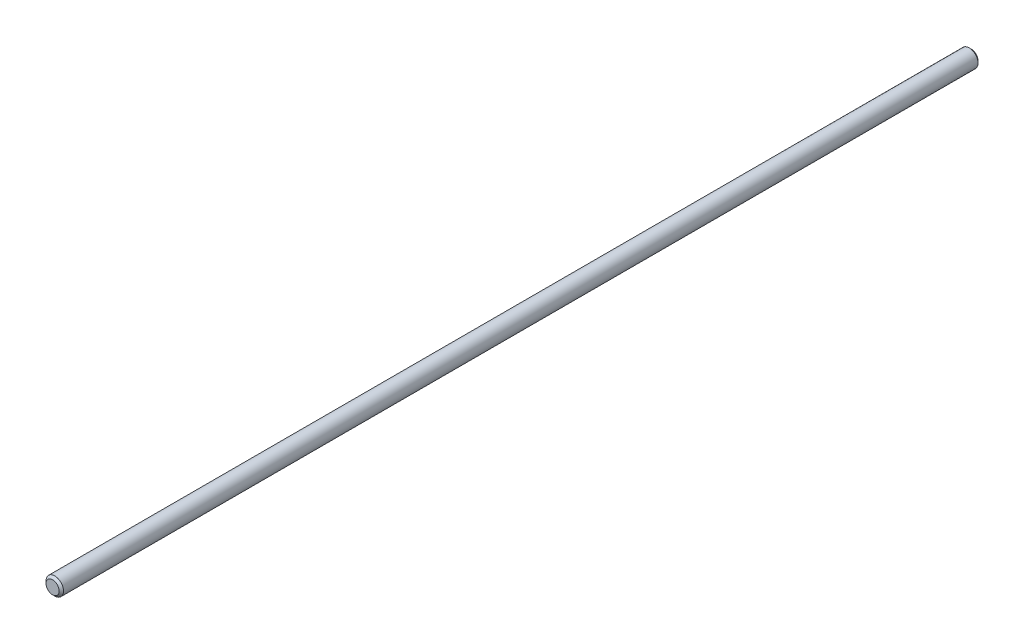
SolidWorks part; units mm, degrees
material "合金钢"
ref_plane "前视基准面" through (0, 0, 0) normal (0, 0, 1) x (1, 0, 0)
ref_plane "上视基准面" through (0, 0, 0) normal (0, 1, 0) x (1, 0, 0)
ref_plane "右视基准面" through (0, 0, 0) normal (1, 0, 0) x (0, 0, -1)
sketch "草图1" plane through (0, 0, 0) normal (0, 0, 1) x (1, 0, 0)
  circle A0 centre (0, 0) radius 4
  dimension "D1" = 8
extrude "凸台-拉伸1" add sketch "草图1" along normal blind 420
chamfer "倒角1" distance 1 angle 45 2 edges at (4, 0, 420) (4, 0, 0)
